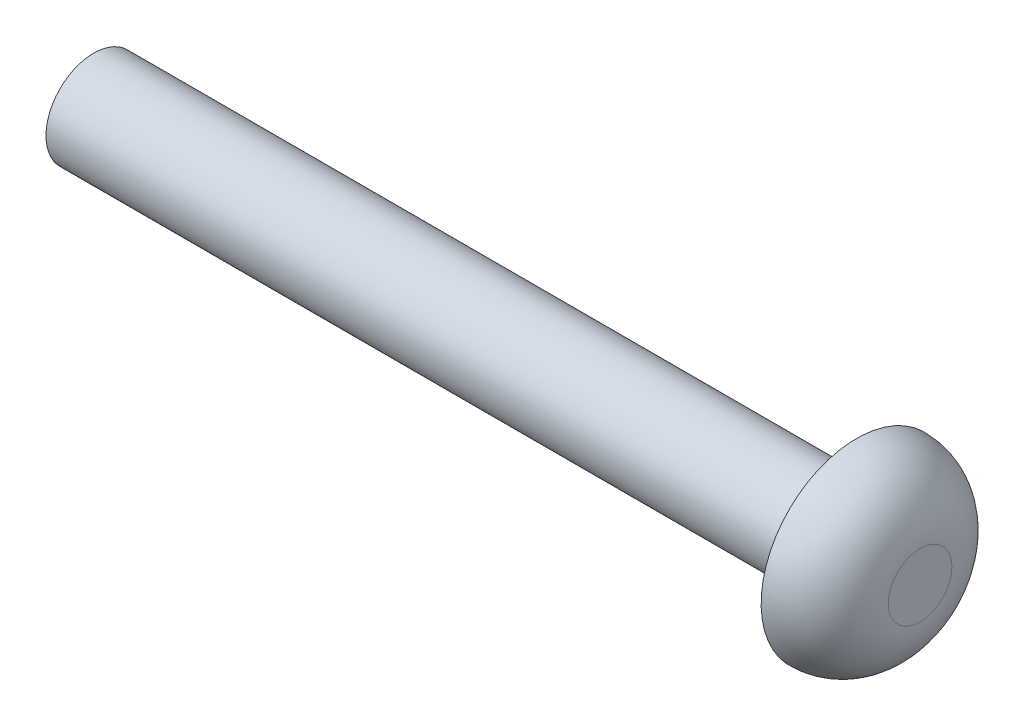
SolidWorks part; units mm, degrees
ref_plane "Front Plane" through (0, 0, 0) normal (0, 0, 1) x (1, 0, 0)
ref_plane "Top Plane" through (0, 0, 0) normal (0, 1, 0) x (1, 0, 0)
ref_plane "Right Plane" through (0, 0, 0) normal (1, 0, 0) x (0, 0, -1)
sketch "Sketch1" plane through (0, 0, 0) normal (0, 0, 1) x (1, 0, 0)
  line L0 (0, 0) -> (0, 6)
  line L1 (0, 6) -> (96, 6)
  line L2 (96, 6) -> (96, 12)
  line L3 (0, 0) -> (104, 0) construction
  line L8 (104, 4) -> (104, 0)
  line L9 (0, 0) -> (104, 0)
  arc A0 (96, 12) -> (104, 4) centre (96, 4) cw
  dimension "D5" = 8
  dimension "D1" = 6
  dimension "D2" = 8
  dimension "D3" = 6
  dimension "D4" = 104
revolve "Revolve1" add sketch "Sketch1" angle 360 about L3
